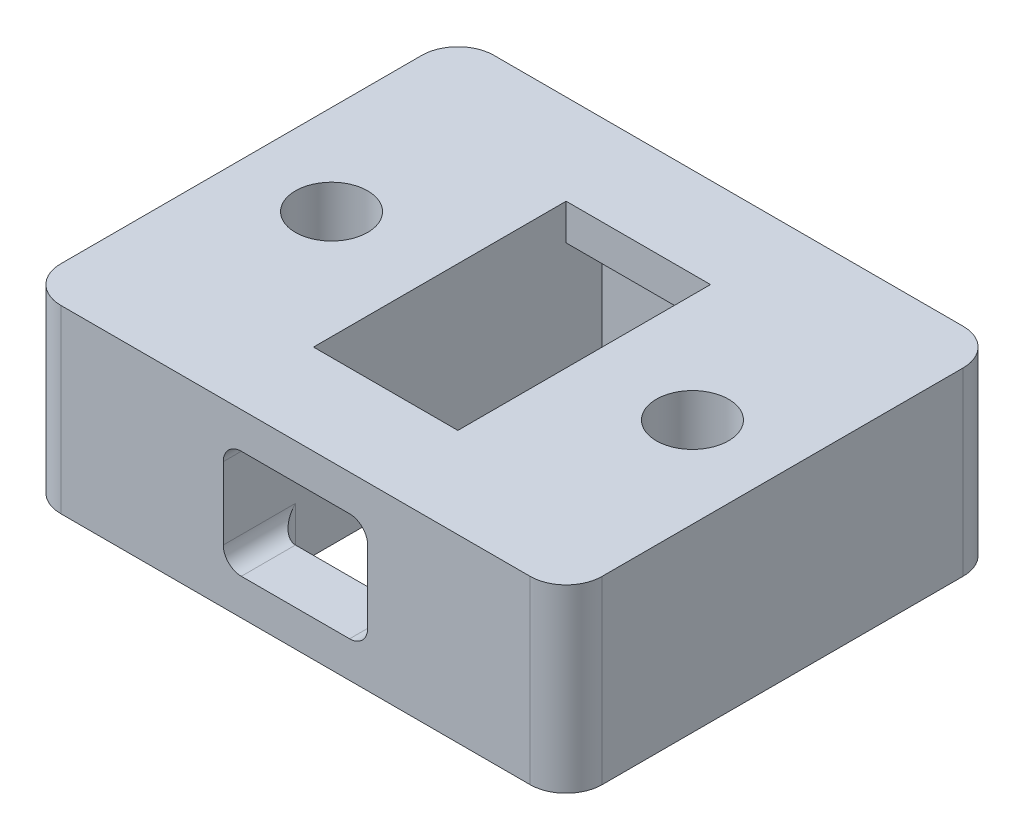
SolidWorks part; units mm, degrees
ref_plane "Front Plane" through (0, 0, 0) normal (0, 0, 1) x (1, 0, 0)
ref_plane "Top Plane" through (0, 0, 0) normal (0, 1, 0) x (1, 0, 0)
ref_plane "Right Plane" through (0, 0, 0) normal (1, 0, 0) x (0, 0, -1)
sketch "Sketch1" plane through (0, 0, 0) normal (0, 1, 0) x (1, 0, 0)
  line L1 (-5.08, 11.43) -> (5.08, 11.43)
  line L2 (-5.08, 11.43) -> (-5.08, -11.43)
  line L3 (-5.08, -11.43) -> (5.08, -11.43)
  line L4 (5.08, 11.43) -> (5.08, -11.43)
  line L5 (-5.08, 11.43) -> (5.08, -11.43) construction
  line L6 (-5.08, -11.43) -> (5.08, 11.43) construction
  line L7 (-19.05, 15.24) -> (19.05, 15.24)
  line L8 (-19.05, 15.24) -> (-19.05, -15.24)
  line L9 (-19.05, -15.24) -> (19.05, -15.24)
  line L10 (19.05, 15.24) -> (19.05, -15.24)
  line L11 (-19.05, 15.24) -> (19.05, -15.24) construction
  line L12 (-19.05, -15.24) -> (19.05, 15.24) construction
  circle A0 centre (-12.7, 0) radius 2.54
  circle A1 centre (12.7, 0) radius 2.54
  point P0 (0, 0)
  point P6 (0, 0)
  point P15 (12.7, 0)
  dimension "D5" = 5.08
  dimension "D6" = 5.08
  dimension "D1" = 10.16
  dimension "D2" = 22.86
  dimension "D3" = 12.7
  dimension "D4" = 12.7
  dimension "D7" = 38.1
  dimension "D8" = 30.48
extrude "Boss-Extrude1" add sketch "Sketch1" against normal blind 12.7 contours L10 L7 L8 L9 A1 A0 L1 L4 L3 L2
sketch "Sketch2" plane through (0, 0, -11.43) normal (0, 0, 1) x (1, 0, 0)
  line L0 (5.08, -12.7) -> (5.08, 0) construction
  line L1 (-5.08, 0) -> (5.08, 0)
  line L2 (-5.08, 0) -> (-5.08, -2.54)
  line L3 (-5.08, -2.54) -> (5.08, -2.54)
  line L4 (5.08, 0) -> (5.08, -2.54)
  dimension "D1" = 2.54
extrude "Boss-Extrude2" add sketch "Sketch2" along normal blind 2.54
sketch "Sketch3" plane through (0, 0, 11.43) normal (0, 0, -1) x (-1, 0, 0)
  line L0 (-5.08, -12.7) -> (-5.08, 0) construction
  line L1 (5.08, 0) -> (-5.08, 0)
  line L2 (5.08, 0) -> (5.08, -2.54)
  line L3 (5.08, -2.54) -> (-5.08, -2.54)
  line L4 (-5.08, 0) -> (-5.08, -2.54)
  dimension "D1" = 2.54
extrude "Boss-Extrude3" add sketch "Sketch3" along normal blind 2.54
fillet "Fillet1" radius 2.54 4 edges at (-19.05, -6.35, 15.24) (19.05, -6.35, 15.24) (19.05, -6.35, -15.24) (-19.05, -6.35, -15.24)
sketch "Sketch4" plane through (0, 0, 11.43) normal (0, 0, -1) x (-1, 0, 0)
  line L6 (5.08, -12.7) -> (5.08, -2.54) construction
  line L7 (-5.08, -2.54) -> (5.08, -2.54)
  line L8 (-5.08, -2.54) -> (-5.08, -10.16)
  line L9 (-5.08, -10.16) -> (5.08, -10.16)
  line L10 (5.08, -2.54) -> (5.08, -10.16)
  dimension "D1" = 7.62
extrude "Cut-Extrude1" cut sketch "Sketch4" against normal through all
fillet "Fillet2" radius 1.27 6 edges at (5.08, -11.43, 11.43) (-5.08, -11.43, 11.43) (5.08, -10.16, 13.335) (-5.08, -10.16, 13.335) (-5.08, -2.54, 12.065) (5.08, -2.54, 12.065)
